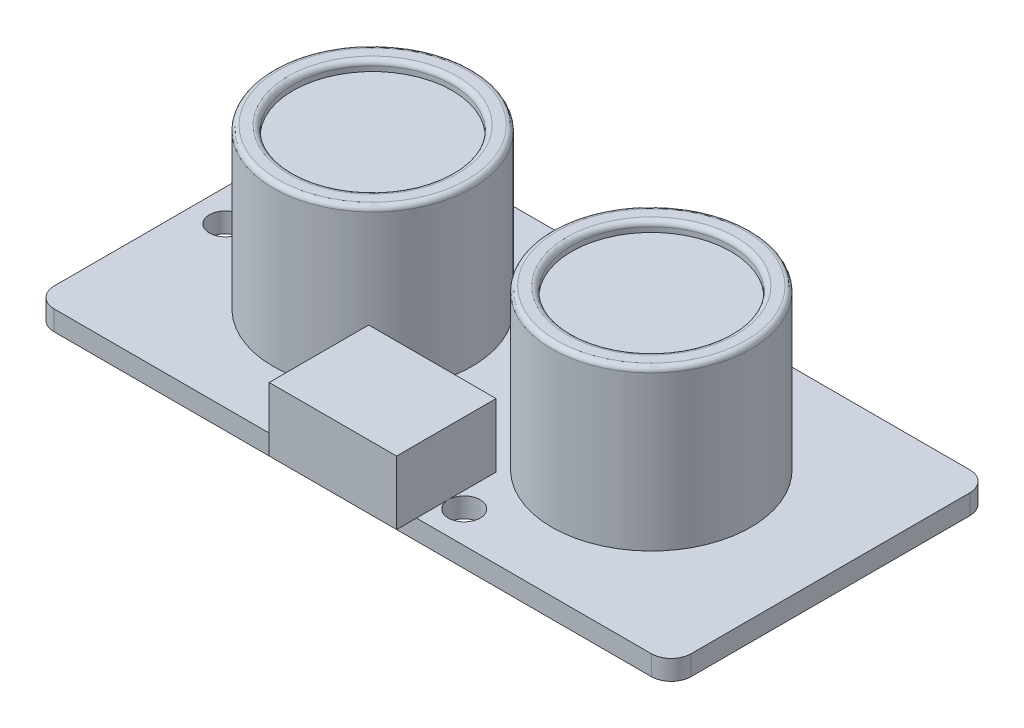
SolidWorks part; units mm, degrees
ref_plane "Front Plane" through (0, 0, 0) normal (0, 0, 1) x (1, 0, 0)
ref_plane "Top Plane" through (0, 0, 0) normal (0, 1, 0) x (1, 0, 0)
ref_plane "Right Plane" through (0, 0, 0) normal (1, 0, 0) x (0, 0, -1)
sketch "Sketch5" plane through (0, 0, 0) normal (0, 1, 0) x (1, 0, 0)
  line L1 (-25.4, -12.7) -> (25.4, -12.7)
  line L2 (-25.4, -12.7) -> (-25.4, 12.7)
  line L3 (-25.4, 12.7) -> (25.4, 12.7)
  line L4 (25.4, -12.7) -> (25.4, 12.7)
  line L5 (-25.4, -12.7) -> (25.4, 12.7) construction
  line L6 (-25.4, 12.7) -> (25.4, -12.7) construction
  point P0 (0, 0)
  dimension "D1" = 50.8
  dimension "D2" = 25.4
extrude "Boss-Extrude4" add sketch "Sketch5" against normal blind 1.5875
fillet "Fillet1" radius 1.5875 4 edges at (25.4, -0.7937, 12.7) (25.4, -0.7937, -12.7) (-25.4, -0.7937, 12.7) (-25.4, -0.7937, -12.7)
sketch "Sketch6" plane through (0, 0, 0) normal (0, 1, 0) x (1, 0, 0)
  line L0 (-22.86, 0) -> (6.35, 0) construction
  line L1 (6.35, 10.16) -> (6.35, -10.16) construction
  line L2 (-25.4, 11.1125) -> (-25.4, -11.1125) construction
  circle A0 centre (-22.86, 0) radius 1.27
  circle A1 centre (6.35, 10.16) radius 1.27
  circle A2 centre (6.35, -10.16) radius 1.27
  point P6 (6.35, 0)
  dimension "D1" = 2.54
  dimension "D2" = 20.32
  dimension "D3" = 2.54
  dimension "D4" = 31.75
extrude "Cut-Extrude1" cut sketch "Sketch6" against normal through all
sketch "Sketch7" plane through (0, 0, 0) normal (0, 1, 0) x (1, 0, 0)
  line L0 (-11.1125, 0) -> (11.1125, 0) construction
  circle A0 centre (11.1125, 0) radius 7.9375
  circle A1 centre (-11.1125, 0) radius 7.9375
  point P2 (0, 0)
  dimension "D1" = 15.875
  dimension "D2" = 22.225
extrude "Boss-Extrude5" add sketch "Sketch7" along normal blind 12.7
sketch "Sketch8" plane through (0, 12.7, 0) normal (0, 1, 0) x (1, 0, 0)
  circle A0 centre (-11.1125, 0) radius 6.35
  circle A1 centre (-11.1125, 0) radius 7.9375 construction
  circle A2 centre (11.1125, 0) radius 6.35
  dimension "D1" = 1.5875
extrude "Cut-Extrude2" cut sketch "Sketch8" against normal blind 0.7937
fillet "Fillet2" radius 0.3969 4 edges at (11.1125, 12.7, 6.35) (11.1125, 12.7, 7.9375) (-11.1125, 12.7, 6.35) (-11.1125, 12.7, 7.9375)
sketch "Sketch9" plane through (0, 0, 0) normal (0, 1, 0) x (1, 0, 0)
  line L0 (-23.8125, -12.7) -> (23.8125, -12.7) construction
  line L1 (-5.08, -14.2875) -> (5.08, -14.2875)
  line L2 (-5.08, -14.2875) -> (-5.08, -6.35)
  line L3 (-5.08, -6.35) -> (5.08, -6.35)
  line L4 (5.08, -14.2875) -> (5.08, -6.35)
  line L5 (-5.08, -14.2875) -> (5.08, -6.35) construction
  line L6 (-5.08, -6.35) -> (5.08, -14.2875) construction
  point P0 (0, -10.3187)
  dimension "D1" = 10.16
  dimension "D2" = 7.9375
  dimension "D3" = 1.5875
extrude "Boss-Extrude6" add sketch "Sketch9" along normal blind 5.08
sketch "Sketch10" plane through (0, -1.5875, 0) normal (0, -1, 0) x (1, 0, 0)
  line L1 (-19.2677, -5.08) -> (-15.4577, -5.08)
  line L2 (-19.2677, -5.08) -> (-19.2677, 5.08)
  line L3 (-19.2677, 5.08) -> (-15.4577, 5.08)
  line L4 (-15.4577, -5.08) -> (-15.4577, 5.08)
  line L5 (-19.2677, -5.08) -> (-15.4577, 5.08) construction
  line L6 (-19.2677, 5.08) -> (-15.4577, -5.08) construction
  line L7 (12.3758, -1.905) -> (21.2658, -1.905)
  line L8 (12.3758, -1.905) -> (12.3758, 1.905)
  line L9 (12.3758, 1.905) -> (21.2658, 1.905)
  line L10 (21.2658, -1.905) -> (21.2658, 1.905)
  line L11 (12.3758, -1.905) -> (21.2658, 1.905) construction
  line L12 (12.3758, 1.905) -> (21.2658, -1.905) construction
  line L13 (-7.8881, -6.4203) -> (1.0019, -6.4203)
  line L14 (-7.8881, -6.4203) -> (-7.8881, -2.6103)
  line L15 (-7.8881, -2.6103) -> (1.0019, -2.6103)
  line L16 (1.0019, -6.4203) -> (1.0019, -2.6103)
  line L17 (-7.8881, -6.4203) -> (1.0019, -2.6103) construction
  line L18 (-7.8881, -2.6103) -> (1.0019, -6.4203) construction
  circle A0 centre (-11.0756, 7.1141) radius 0.4265
  circle A1 centre (-11.1125, -7.0194) radius 0.4796
  circle A2 centre (11.3645, -7.0194) radius 0.5779
  circle A3 centre (11.3645, 7.1141) radius 0.4815
  point P0 (-17.3627, 0)
  point P5 (16.8208, 0)
  point P14 (-3.4431, -4.5153)
  dimension "D1" = 10.16
  dimension "D2" = 8.89
  dimension "D3" = 8.89
  dimension "D4" = 3.81
  dimension "D5" = 3.81
  dimension "D6" = 3.81
extrude "Boss-Extrude7" add sketch "Sketch10" along normal blind 1.5875
